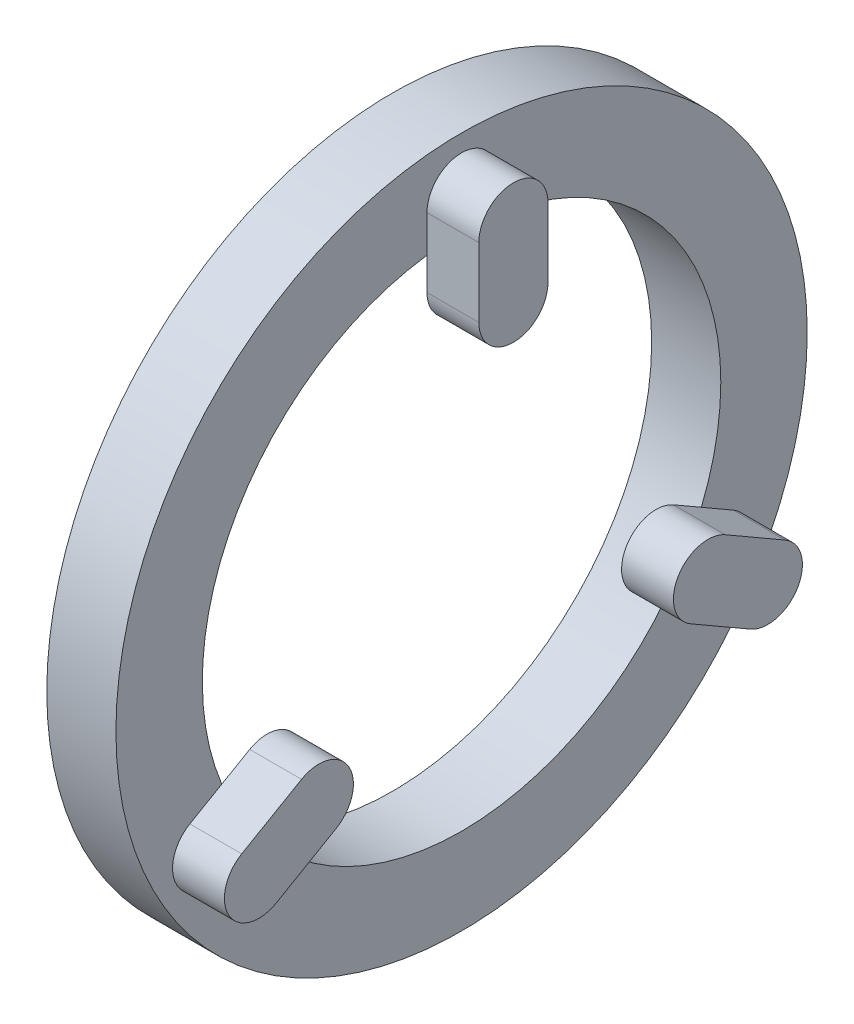
SolidWorks part; units mm, degrees
ref_plane "前视基准面" through (0, 0, 0) normal (0, 0, 1) x (1, 0, 0)
ref_plane "上视基准面" through (0, 0, 0) normal (0, 1, 0) x (1, 0, 0)
ref_plane "右视基准面" through (0, 0, 0) normal (1, 0, 0) x (0, 0, -1)
sketch "草图1" plane through (0, 0, 0) normal (1, 0, 0) x (0, 0, -1)
  circle A0 centre (0, 0) radius 10
extrude "凸台-拉伸1" add sketch "草图1" along normal blind 2
sketch "草图3" plane through (2, 0, 0) normal (1, 0, 0) x (0, 0, -1)
  circle A0 centre (0, 0) radius 7.5
extrude "切除-拉伸1" cut sketch "草图3" against normal blind 12.5
sketch "草图5" plane through (2, 0, 0) normal (1, 0, 0) x (0, 0, -1)
  line L0 (0, 0) -> (0, 8.5)
  line L4 (0, 0) -> (-7.3612, -4.25)
  line L5 (7.3612, -4.25) -> (0, 0)
  line L6 (-7.8612, -3.384) -> (-6.1292, -2.384)
  line L7 (-6.1292, -2.384) -> (-5.1292, -4.116)
  line L8 (-5.1292, -4.116) -> (-6.8612, -5.116)
  line L9 (-6.8612, -5.116) -> (-7.8612, -3.384)
  line L10 (-1, 8.5) -> (-1, 6.5)
  line L11 (-1, 6.5) -> (1, 6.5)
  line L12 (1, 6.5) -> (1, 8.5)
  line L13 (1, 8.5) -> (-1, 8.5)
  line L14 (6.1292, -2.384) -> (7.8612, -3.384)
  line L15 (7.8612, -3.384) -> (6.8612, -5.116)
  line L16 (6.8612, -5.116) -> (5.1292, -4.116)
  line L17 (5.1292, -4.116) -> (6.1292, -2.384)
  circle A0 centre (0, 8.5) radius 1
  circle A1 centre (7.3612, -4.25) radius 1
  circle A2 centre (-7.3612, -4.25) radius 1
  circle A3 centre (-5.6292, -3.25) radius 1
  circle A4 centre (0, 6.5) radius 1
  circle A5 centre (5.6292, -3.25) radius 1
  point P8 (-5.6292, -3.25)
  point P9 (0, 6.5)
  point P10 (5.6292, -3.25)
  dimension "D6" = 2
  dimension "D1" = 120
  dimension "D2" = 120
  dimension "D3" = 8.5
  dimension "D4" = 8.5
  dimension "D5" = 8.5
  dimension "D7" = 2
  dimension "D8" = 2
extrude "凸台-拉伸5" add sketch "草图5" along normal blind 1.5 contours A2 | A3 | L6 L7 L8 L9 | L14 L15 L16 L17 | A1 | A5 | A0 | A4 | L10 L11 L12 L13
